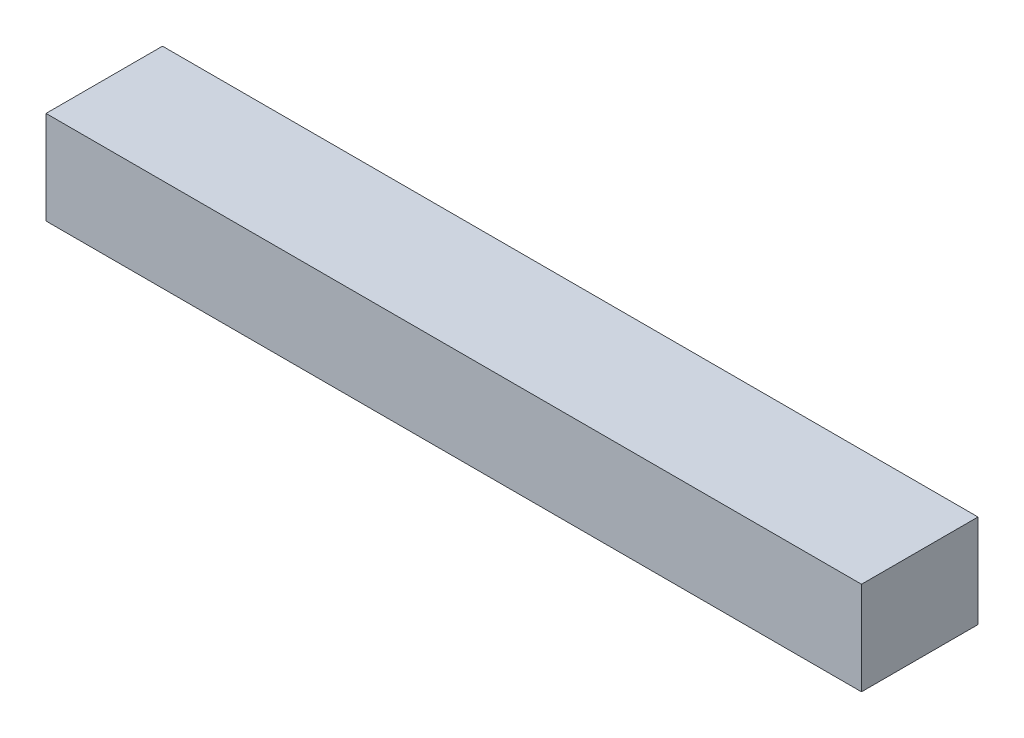
SolidWorks part; units mm, degrees
ref_plane "Front Plane" through (0, 0, 0) normal (0, 0, 1) x (1, 0, 0)
ref_plane "Top Plane" through (0, 0, 0) normal (0, 1, 0) x (1, 0, 0)
ref_plane "Right Plane" through (0, 0, 0) normal (1, 0, 0) x (0, 0, -1)
sketch "Sketch1" plane through (0, 0, 0) normal (1, 0, 0) x (0, 0, -1)
  line L1 (0, 0) -> (10, 0)
  line L2 (0, 0) -> (0, 8)
  line L3 (0, 8) -> (10, 8)
  line L4 (10, 0) -> (10, 8)
  dimension "D1" = 8
  dimension "D2" = 10
extrude "Boss-Extrude1" add sketch "Sketch1" along normal blind 70
